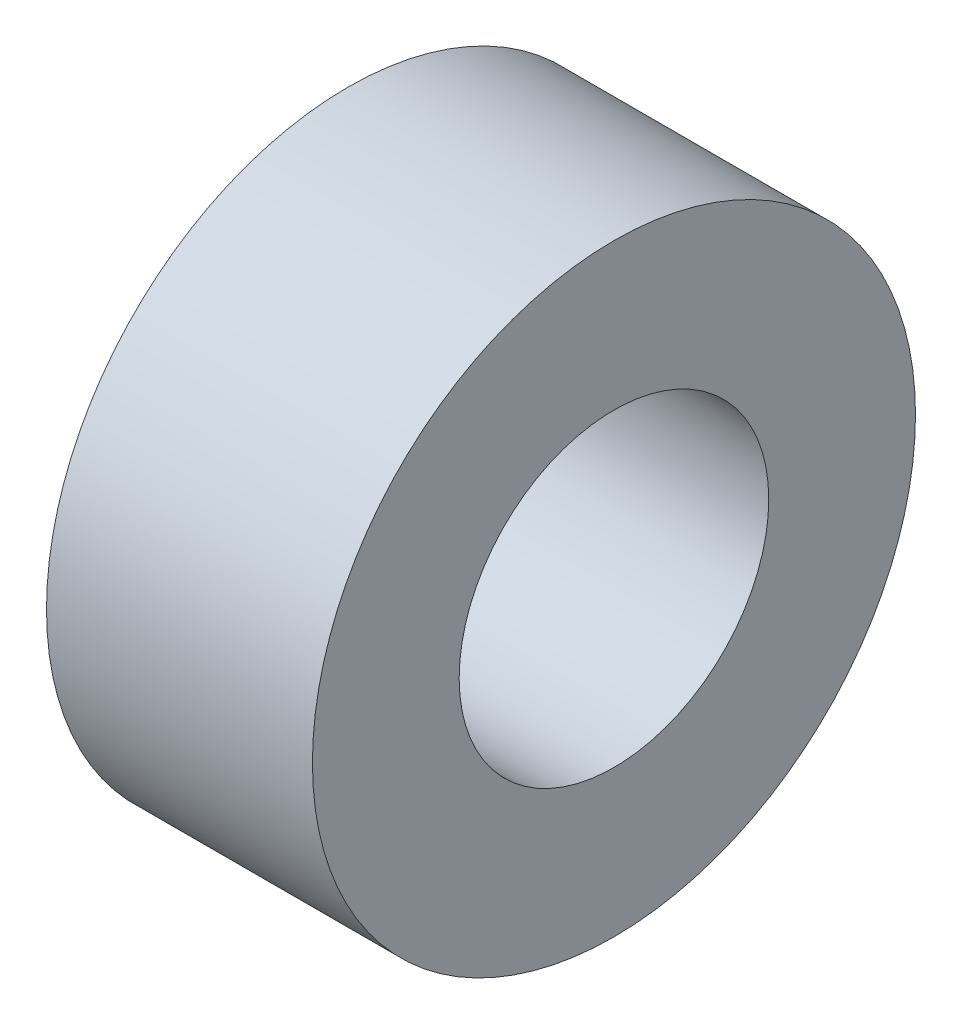
SolidWorks part; units mm, degrees
ref_plane "Front Plane" through (0, 0, 0) normal (0, 0, 1) x (1, 0, 0)
ref_plane "Top Plane" through (0, 0, 0) normal (0, 1, 0) x (1, 0, 0)
ref_plane "Right Plane" through (0, 0, 0) normal (1, 0, 0) x (0, 0, -1)
sketch "Sketch1" plane through (0, 0, 0) normal (1, 0, 0) x (0, 0, -1)
  circle A0 centre (0, 0) radius 7.9375
  dimension "D1" = 15.875
extrude "Boss-Extrude1" add sketch "Sketch1" along normal blind 7 contours A0
sketch "Sketch2" plane through (7, 0, 0) normal (1, 0, 0) x (0, 0, -1)
  circle A0 centre (0, 0) radius 4.075
  dimension "D1" = 8.15
extrude "Cut-Extrude1" cut sketch "Sketch2" against normal blind 15
